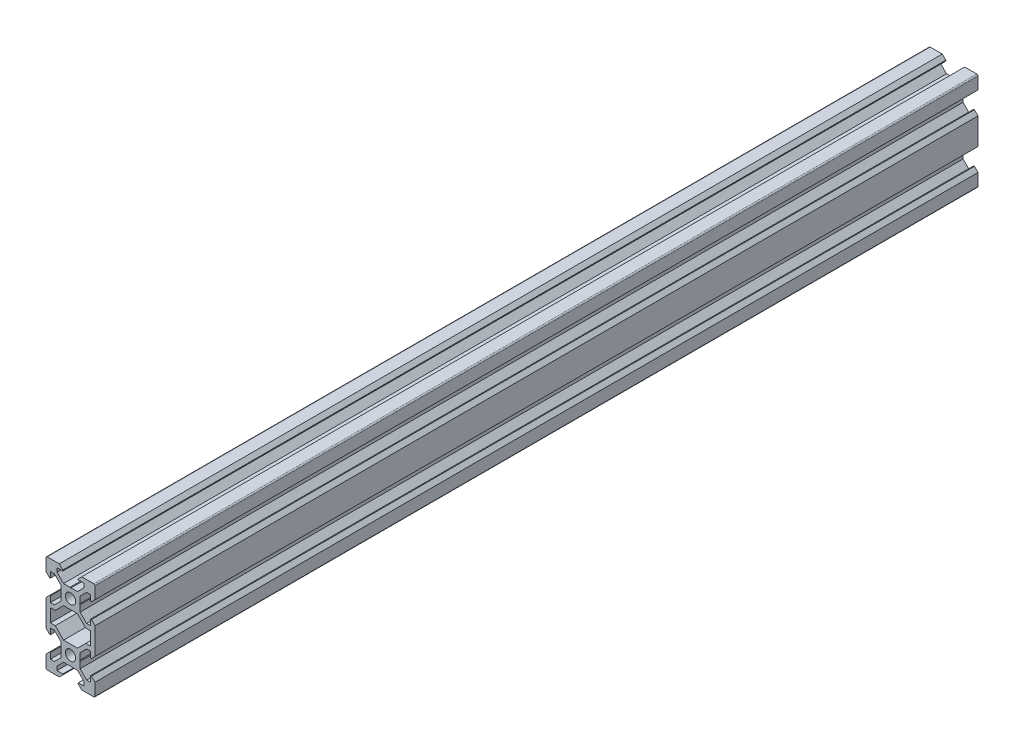
SolidWorks part; units mm, degrees
material "6061-T6 (SS)"
ref_plane "Front Plane" through (0, 0, 0) normal (0, 0, 1) x (1, 0, 0)
ref_plane "Top Plane" through (0, 0, 0) normal (0, 1, 0) x (1, 0, 0)
ref_plane "Right Plane" through (0, 0, 0) normal (1, 0, 0) x (0, 0, -1)
sketch "Sketch1" plane through (0, 0, 0) normal (0, 0, 1) x (1, 0, 0)
  line L0 (0, 0) -> (10, 0) construction
  line L1 (9.5, -20) -> (-9.5, -20)
  line L2 (10, -19.5) -> (10, 19.5)
  line L3 (9.5, 20) -> (-9.5, 20)
  line L4 (-10, -19.5) -> (-10, 19.5)
  line L5 (10, -20) -> (-10, 20) construction
  line L6 (10, 20) -> (-10, -20) construction
  circle A0 centre (0, 10) radius 2.1
  circle A1 centre (0, -10) radius 2.1
  arc A2 (-9.5, -20) -> (-10, -19.5) centre (-9.5, -19.5) cw
  arc A3 (9.5, -20) -> (10, -19.5) centre (9.5, -19.5) ccw
  arc A4 (10, 19.5) -> (9.5, 20) centre (9.5, 19.5) ccw
  arc A5 (-9.5, 20) -> (-10, 19.5) centre (-9.5, 19.5) ccw
  point P0 (0, 0)
  line B0 (0, 10) -> (0, 20) construction
  line B1 (0, 13.69) -> (-0.21, 13.9)
  line B2 (-0.21, 13.9) -> (-2.8393, 13.9)
  line B3 (-2.8393, 13.9) -> (-5.5, 16.5607)
  line B4 (-5.5, 16.5607) -> (-5.5, 18.2)
  line B5 (-5.5, 18.2) -> (-3.125, 18.2)
  line B6 (-3.125, 18.2) -> (-3.125, 18.545)
  line B7 (-3.125, 18.545) -> (-4.58, 20)
  line B8 (-4.58, 20) -> (4.58, 20)
  line B9 (0, 10) -> (-5.9132, 15.9132) construction
  line B10 (3.125, 18.545) -> (4.58, 20)
  line B11 (3.125, 18.2) -> (3.125, 18.545)
  line B12 (5.5, 18.2) -> (3.125, 18.2)
  line B13 (5.5, 16.5607) -> (5.5, 18.2)
  line B14 (2.8393, 13.9) -> (5.5, 16.5607)
  line B15 (0.21, 13.9) -> (2.8393, 13.9)
  line B16 (0, 13.69) -> (0.21, 13.9)
  line B17 (0, 10) -> (-10, 10) construction
  line B18 (-3.69, 10) -> (-3.9, 9.79)
  line B19 (-3.9, 9.79) -> (-3.9, 7.1607)
  line B20 (-3.9, 7.1607) -> (-6.5607, 4.5)
  line B21 (-6.5607, 4.5) -> (-8.2, 4.5)
  line B22 (-8.2, 4.5) -> (-8.2, 6.875)
  line B23 (-8.2, 6.875) -> (-8.545, 6.875)
  line B24 (-8.545, 6.875) -> (-10, 5.42)
  line B25 (-10, 5.42) -> (-10, 14.58)
  line B26 (0, 10) -> (-5.9132, 4.0868) construction
  line B27 (-8.545, 13.125) -> (-10, 14.58)
  line B28 (-8.2, 13.125) -> (-8.545, 13.125)
  line B29 (-8.2, 15.5) -> (-8.2, 13.125)
  line B30 (-6.5607, 15.5) -> (-8.2, 15.5)
  line B31 (-3.9, 12.8393) -> (-6.5607, 15.5)
  line B32 (-3.9, 10.21) -> (-3.9, 12.8393)
  line B33 (-3.69, 10) -> (-3.9, 10.21)
  line B34 (0, -10) -> (-10, -10) construction
  line B35 (-3.69, -10) -> (-3.9, -10.21)
  line B36 (-3.9, -10.21) -> (-3.9, -12.8393)
  line B37 (-3.9, -12.8393) -> (-6.5607, -15.5)
  line B38 (-6.5607, -15.5) -> (-8.2, -15.5)
  line B39 (-8.2, -15.5) -> (-8.2, -13.125)
  line B40 (-8.2, -13.125) -> (-8.545, -13.125)
  line B41 (-8.545, -13.125) -> (-10, -14.58)
  line B42 (-10, -14.58) -> (-10, -5.42)
  line B43 (0, -10) -> (-5.9132, -15.9132) construction
  line B44 (-8.545, -6.875) -> (-10, -5.42)
  line B45 (-8.2, -6.875) -> (-8.545, -6.875)
  line B46 (-8.2, -4.5) -> (-8.2, -6.875)
  line B47 (-6.5607, -4.5) -> (-8.2, -4.5)
  line B48 (-3.9, -7.1607) -> (-6.5607, -4.5)
  line B49 (-3.9, -9.79) -> (-3.9, -7.1607)
  line B50 (-3.69, -10) -> (-3.9, -9.79)
  line B51 (0, -10) -> (0, -20) construction
  line B52 (0, -13.69) -> (0.21, -13.9)
  line B53 (0.21, -13.9) -> (2.8393, -13.9)
  line B54 (2.8393, -13.9) -> (5.5, -16.5607)
  line B55 (5.5, -16.5607) -> (5.5, -18.2)
  line B56 (5.5, -18.2) -> (3.125, -18.2)
  line B57 (3.125, -18.2) -> (3.125, -18.545)
  line B58 (3.125, -18.545) -> (4.58, -20)
  line B59 (4.58, -20) -> (-4.58, -20)
  line B60 (0, -10) -> (5.9132, -15.9132) construction
  line B61 (-3.125, -18.545) -> (-4.58, -20)
  line B62 (-3.125, -18.2) -> (-3.125, -18.545)
  line B63 (-5.5, -18.2) -> (-3.125, -18.2)
  line B64 (-5.5, -16.5607) -> (-5.5, -18.2)
  line B65 (-2.8393, -13.9) -> (-5.5, -16.5607)
  line B66 (-0.21, -13.9) -> (-2.8393, -13.9)
  line B67 (0, -13.69) -> (-0.21, -13.9)
  line B68 (0, -10) -> (10, -10) construction
  line B69 (3.69, -10) -> (3.9, -9.79)
  line B70 (3.9, -9.79) -> (3.9, -7.1607)
  line B71 (3.9, -7.1607) -> (6.5607, -4.5)
  line B72 (6.5607, -4.5) -> (8.2, -4.5)
  line B73 (8.2, -4.5) -> (8.2, -6.875)
  line B74 (8.2, -6.875) -> (8.545, -6.875)
  line B75 (8.545, -6.875) -> (10, -5.42)
  line B76 (10, -5.42) -> (10, -14.58)
  line B77 (0, -10) -> (5.9132, -4.0868) construction
  line B78 (8.545, -13.125) -> (10, -14.58)
  line B79 (8.2, -13.125) -> (8.545, -13.125)
  line B80 (8.2, -15.5) -> (8.2, -13.125)
  line B81 (6.5607, -15.5) -> (8.2, -15.5)
  line B82 (3.9, -12.8393) -> (6.5607, -15.5)
  line B83 (3.9, -10.21) -> (3.9, -12.8393)
  line B84 (3.69, -10) -> (3.9, -10.21)
  line B85 (0, 10) -> (10, 10) construction
  line B86 (3.69, 10) -> (3.9, 10.21)
  line B87 (3.9, 10.21) -> (3.9, 12.8393)
  line B88 (3.9, 12.8393) -> (6.5607, 15.5)
  line B89 (6.5607, 15.5) -> (8.2, 15.5)
  line B90 (8.2, 15.5) -> (8.2, 13.125)
  line B91 (8.2, 13.125) -> (8.545, 13.125)
  line B92 (8.545, 13.125) -> (10, 14.58)
  line B93 (10, 14.58) -> (10, 5.42)
  line B94 (0, 10) -> (5.9132, 15.9132) construction
  line B95 (8.545, 6.875) -> (10, 5.42)
  line B96 (8.2, 6.875) -> (8.545, 6.875)
  line B97 (8.2, 4.5) -> (8.2, 6.875)
  line B98 (6.5607, 4.5) -> (8.2, 4.5)
  line B99 (3.9, 7.1607) -> (6.5607, 4.5)
  line B100 (3.9, 9.79) -> (3.9, 7.1607)
  line B101 (3.69, 10) -> (3.9, 9.79)
  line B102 (-8.2, -2.7) -> (-8.2, 2.7)
  line B103 (-8.2, 2.7) -> (-6.2393, 2.7)
  line B104 (-6.2393, 2.7) -> (-2.8393, 6.1)
  line B105 (-2.8393, 6.1) -> (2.8393, 6.1)
  line B106 (0, 6.1) -> (0, 0) construction
  line B107 (0, 0) -> (-8.2, 0) construction
  line B108 (6.2393, 2.7) -> (2.8393, 6.1)
  line B109 (8.2, 2.7) -> (6.2393, 2.7)
  line B110 (8.2, -2.7) -> (8.2, 2.7)
  line B111 (8.2, -2.7) -> (6.2393, -2.7)
  line B112 (6.2393, -2.7) -> (2.8393, -6.1)
  line B113 (-2.8393, -6.1) -> (2.8393, -6.1)
  line B114 (-6.2393, -2.7) -> (-2.8393, -6.1)
  line B115 (-8.2, -2.7) -> (-6.2393, -2.7)
  line B116 (0, 6.1) -> (0, 10) construction
  line B117 (0, 10) -> (-5.0927, 4.9073) construction
  dimension "D4" = 4.2
  dimension "D5" = 0.5
  dimension "D1" = 20
  dimension "D2" = 40
  dimension "D3" = 20
sketch_block_instance "V Slot 1-4"
sketch_block "V Slot 1" parameters "D1"=10, "D2"=11, "D3"=4.3, "D4"=1.8, "D5"=0.21, "D6"=45, "D7"=9.16, "D8"=1.5, "D9"=6.25
sketch_block_instance "V Slot 1-5"
sketch_block_instance "V Slot 1-6"
sketch_block_instance "V Slot 1-7"
sketch_block_instance "V Slot 1-8"
sketch_block_instance "V Slot 1-9"
sketch_block_instance "Center Cutout 1-1"
sketch_block "Center Cutout 1" parameters "D1"=5.4, "D2"=12.2, "D3"=8.2, "D4"=45, "D5"=10, "D6"=1.5
extrude "Boss-Extrude1" add sketch "Sketch1" along normal mid plane 360.4 contours B101 B86 B87 B88 B89 B90 B91 B92 L2 A4 L3 B10 B11 B12 B13 B14 B15 B16 B1 B2 B3 B4 B5 B6 B7 A5 L4 B27 B28 B29 B30 B31 B32 B33 B18 B19 B20 B21 B22 B23 B24 B44 B45 B46 B47 B48 B49 B50 B35
